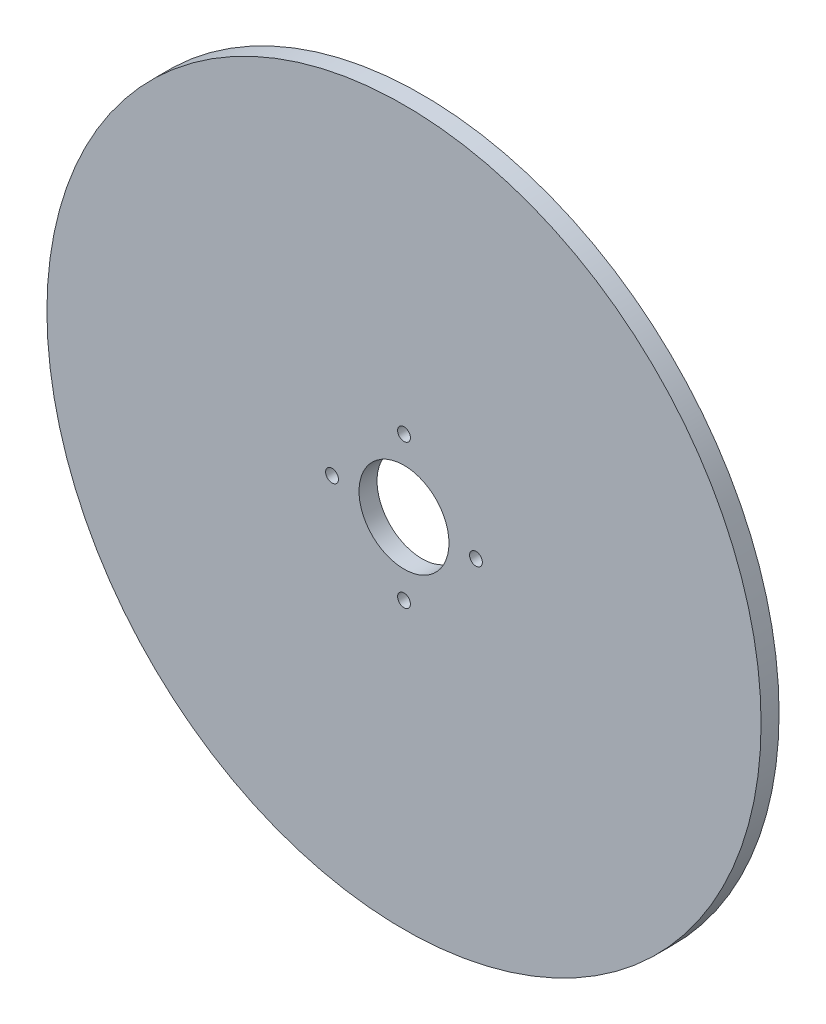
SolidWorks part; units mm, degrees
material "6061 Alloy"
ref_plane "Front Plane" through (0, 0, 0) normal (0, 0, 1) x (1, 0, 0)
ref_plane "Top Plane" through (0, 0, 0) normal (0, 1, 0) x (1, 0, 0)
ref_plane "Right Plane" through (0, 0, 0) normal (1, 0, 0) x (0, 0, -1)
sketch "Sketch1" plane through (0, 0, 0) normal (0, 0, 1) x (1, 0, 0)
  circle A0 centre (0, 0) radius 63.0174
  circle A1 centre (0, 0) radius 7.9375
  dimension "D1" = 126.0348
  dimension "D2" = 15.875
extrude "Boss-Extrude1" add sketch "Sketch1" along normal blind 3.175
hole_wizard "Tap Drill for #4-40 Tap1" positions "Sketch2" profile "Sketch3" hole size "#4-40" standard "ANSI Inch"
sketch "Sketch2" plane through (0, 0, 3.175) normal (0, 0, 1) x (1, 0, 0)
  point P0 (0, 12.7)
  point P2 (0, -12.7)
  point P4 (12.7, 0)
  point P6 (-12.7, 0)
  dimension "D1" = 12.7
  dimension "D2" = 12.7
  dimension "D3" = 12.7
  dimension "D4" = 12.7
sketch "Sketch3" plane through (0, 12.7, 3.175) normal (1, 0, 0) x (0, -1, 0)
  line L0 (0, 0) -> (0, 4.6792)
  line L1 (0, 4.6792) -> (1.1303, 4)
  line L2 (1.1303, 4) -> (1.1303, 0)
  line L5 (1.1303, 0) -> (0, 0)
  line L10 (0, 4.6792) -> (-1.1303, 4) construction
  line L11 (0, -6.35) -> (0, 107.95) construction
  dimension "Hole Dia." = 2.2606
  dimension "Hole Depth" = 4
  dimension "Drill Angle" = 118
